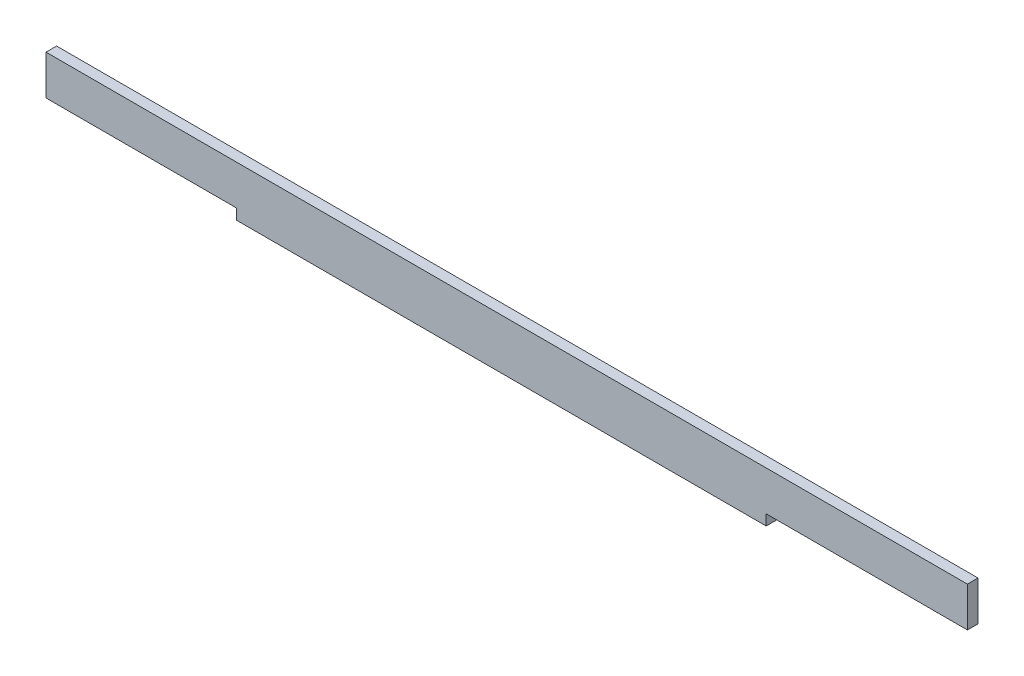
SolidWorks part; units mm, degrees
ref_plane "Front Plane" through (0, 0, 0) normal (0, 0, 1) x (1, 0, 0)
ref_plane "Top Plane" through (0, 0, 0) normal (0, 1, 0) x (1, 0, 0)
ref_plane "Right Plane" through (0, 0, 0) normal (1, 0, 0) x (0, 0, -1)
sketch "Sketch2" plane through (0, 0, 0) normal (0, 0, 1) x (1, 0, 0)
  line L0 (-171.637, 1.5462) -> (-99.637, 1.5462)
  line L1 (-99.637, 1.5462) -> (-99.637, -2.4538)
  line L2 (-99.637, -2.4538) -> (100.363, -2.4538)
  line L3 (100.363, 1.5462) -> (100.363, -2.4538)
  line L4 (100.363, 1.5462) -> (176.363, 1.5462)
  line L5 (176.363, 16.5462) -> (-171.637, 16.5462)
  line L6 (-171.637, 16.5462) -> (-171.637, 1.5462)
  line L7 (176.363, 16.5462) -> (176.363, 1.5462)
  dimension "D1" = 72
  dimension "D2" = 200
  dimension "D3" = 76
extrude "Boss-Extrude1" add sketch "Sketch2" along normal blind 4
